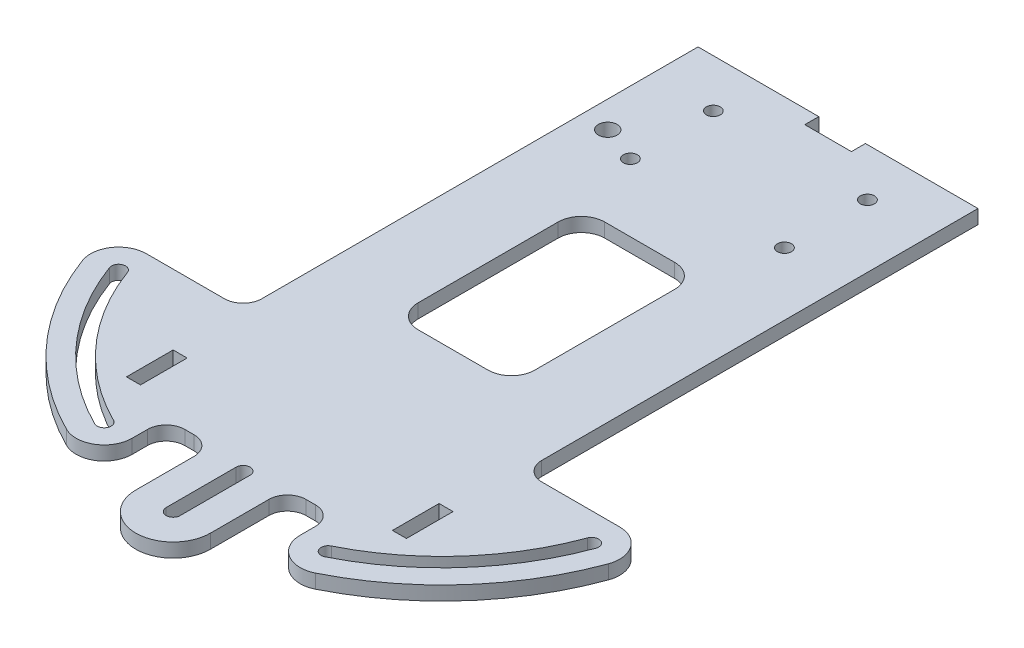
SolidWorks part; units mm, degrees
material "Acrílico (Impacto medio-alto)"
ref_plane "Alzado" through (0, 0, 0) normal (0, 0, 1) x (1, 0, 0)
ref_plane "Planta" through (0, 0, 0) normal (0, 1, 0) x (1, 0, 0)
ref_plane "Vista lateral" through (0, 0, 0) normal (1, 0, 0) x (0, 0, -1)
sketch "Croquis1" plane through (0, 0, 0) normal (0, 1, 0) x (1, 0, 0)
  line L0 (-4.124, 62.5) -> (-4.124, 59.5) construction
  line L2 (-30, -21.9752) -> (-30, 62.5)
  line L3 (-30, 62.5) -> (-4.124, 62.5)
  line L4 (30, -21.9752) -> (30, 62.5)
  line L5 (-30, -62.5) -> (30, 62.5) construction
  line L6 (-30, 62.5) -> (30, -62.5) construction
  line L7 (5.876, 59.5) -> (-4.124, 59.5) construction
  line L8 (5.876, 62.5) -> (5.876, 59.5) construction
  line L9 (-4.124, 62.5) -> (-4.124, 59.5)
  line L10 (5.876, 59.5) -> (-4.124, 59.5)
  line L11 (5.876, 62.5) -> (5.876, 59.5)
  line L12 (5.876, 62.5) -> (30, 62.5)
  line L13 (30, -50) -> (27, -50) construction
  line L14 (27, -60) -> (27, -50) construction
  line L15 (30, -60) -> (27, -60) construction
  line L16 (30, -60) -> (30, -50) construction
  line L17 (-27, -60) -> (-27, -50) construction
  line L18 (-27, -60) -> (-30, -60) construction
  line L19 (-30, -60) -> (-30, -50) construction
  line L20 (-27, -50) -> (-30, -50) construction
  line L21 (30, -50) -> (27, -50)
  line L22 (27, -60) -> (27, -50)
  line L23 (30, -60) -> (27, -60)
  line L24 (30, -60) -> (30, -50)
  line L25 (-27, -60) -> (-27, -50)
  line L26 (-27, -60) -> (-30, -60)
  line L27 (-30, -60) -> (-30, -50)
  line L28 (-27, -50) -> (-30, -50)
  line L29 (1.5, -65) -> (1.5, -80)
  line L30 (-1.5, -65) -> (-1.5, -80)
  line L37 (0, -53.3691) -> (0, -93.3691) construction
  line L39 (-30, -21.9752) -> (-30, -31)
  line L40 (7.5, -20) -> (-7.5, -20)
  line L41 (12.5, -15) -> (12.5, 15)
  line L42 (7.5, 20) -> (-7.5, 20)
  line L43 (-12.5, -15) -> (-12.5, 15)
  line L44 (12.5, -20) -> (-12.5, 20) construction
  line L45 (12.5, 20) -> (-12.5, -20) construction
  line L46 (-34, -35) -> (-50.6997, -35)
  line L47 (-18, -70.7847) -> (-18, -67.5)
  line L49 (0, -80) -> (0, -53.3691) construction
  line L50 (-8, -80) -> (-8, -67.5)
  line L51 (8, -80) -> (8, -67.5)
  line L53 (18, -70.7847) -> (18, -67.5)
  line L54 (34, -35) -> (50.6997, -35)
  line L55 (30, -21.9752) -> (30, -31)
  line L56 (-14, -63.5) -> (-12, -63.5)
  line L57 (12, -63.5) -> (14, -63.5)
  circle A3 centre (-24.3, 37.4392) radius 2
  circle A4 centre (16.54, 52.2601) radius 1.5 construction
  circle A5 centre (16.54, 34.4801) radius 1.5 construction
  circle A16 centre (-16.48, 34.4801) radius 1.5 construction
  circle A18 centre (-16.48, 52.2601) radius 1.5 construction
  circle A19 centre (16.54, 52.2601) radius 1.5
  circle A20 centre (16.54, 34.4801) radius 1.5
  circle A25 centre (-16.48, 34.4801) radius 1.5
  circle A26 centre (-16.48, 52.2601) radius 1.5
  arc A27 (-50.6997, -41) -> (-24, -70.7847) centre (0, -22.4112) ccw construction
  arc A32 (-56.3329, -43.0654) -> (-26.6667, -76.1595) centre (0, -22.4112) ccw
  arc A37 (24, -70.7847) -> (50.6997, -41) centre (0, -22.4112) ccw construction
  arc A38 (-1.5, -80) -> (1.5, -80) centre (0, -80) ccw
  arc A39 (1.5, -65) -> (-1.5, -65) centre (0, -65) ccw
  arc A40 (7.5, -20) -> (12.5, -15) centre (7.5, -15) ccw
  arc A41 (-7.5, -20) -> (-12.5, -15) centre (-7.5, -15) cw
  arc A42 (-7.5, 20) -> (-12.5, 15) centre (-7.5, 15) ccw
  arc A43 (12.5, 15) -> (7.5, 20) centre (7.5, 15) ccw
  arc A45 (-50.6997, -35) -> (-56.3329, -43.0654) centre (-50.6997, -41) ccw
  arc A46 (-26.6667, -76.1595) -> (-18, -70.7847) centre (-24, -70.7847) ccw
  arc A47 (-8, -80) -> (8, -80) centre (0, -80) ccw
  arc A49 (26.6667, -76.1595) -> (18, -70.7847) centre (24, -70.7847) cw
  arc A50 (56.3329, -43.0654) -> (26.6667, -76.1595) centre (0, -22.4112) cw
  arc A51 (50.6997, -35) -> (56.3329, -43.0654) centre (50.6997, -41) cw
  arc A52 (-24, -70.7847) -> (-50.6997, -41) centre (0, -22.4112) cw construction
  arc A53 (-52.108, -41.5164) -> (-24.6667, -72.1284) centre (0, -22.4112) ccw
  arc A54 (-49.2913, -40.4836) -> (-23.3333, -69.441) centre (0, -22.4112) ccw
  arc A55 (-49.2913, -40.4836) -> (-52.108, -41.5164) centre (-50.6997, -41) ccw
  arc A56 (-24.6667, -72.1284) -> (-23.3333, -69.441) centre (-24, -70.7847) ccw
  arc A57 (52.108, -41.5164) -> (24.6667, -72.1284) centre (0, -22.4112) cw
  arc A62 (18, -67.5) -> (14, -63.5) centre (14, -67.5) ccw
  arc A63 (12, -63.5) -> (8, -67.5) centre (12, -67.5) ccw
  arc A64 (-12, -63.5) -> (-8, -67.5) centre (-12, -67.5) cw
  arc A65 (-14, -63.5) -> (-18, -67.5) centre (-14, -67.5) ccw
  arc A66 (30, -31) -> (34, -35) centre (34, -31) ccw
  arc A67 (-30, -31) -> (-34, -35) centre (-34, -31) cw
  arc A68 (49.2913, -40.4836) -> (23.3333, -69.441) centre (0, -22.4112) cw
  arc A69 (49.2913, -40.4836) -> (52.108, -41.5164) centre (50.6997, -41) cw
  arc A70 (24.6667, -72.1284) -> (23.3333, -69.441) centre (24, -70.7847) cw
  arc A71 (50.6997, -41) -> (24, -70.7847) centre (0, -22.4112) cw construction
  point P0 (0, 0)
  point P39 (-48.2444, -70.4426)
  point P42 (0, -65)
  point P47 (-40.2093, -58.4557)
  point P51 (40.2093, -58.4557)
  point P52 (0, 0)
  point P104 (30, -35)
  point P107 (-30, -35)
  dimension "D3" = 4
  dimension "D4" = 1.5
  dimension "D5" = 15
  dimension "D7" = 25
  dimension "D11" = 60
  dimension "D6" = 65
  dimension "D9" = 5
  dimension "D12" = 4
  dimension "D13" = 40
  dimension "D15" = 8
  dimension "D16" = 6
  dimension "D17" = 80
  dimension "D19" = 40
  dimension "D1" = 125
  dimension "D2" = 60
  dimension "D8" = 40
  dimension "D10" = 35
  dimension "D14" = 10
  dimension "D18" = 3
extrude "Saliente-Extruir1" add sketch "Croquis1" along normal blind 3
